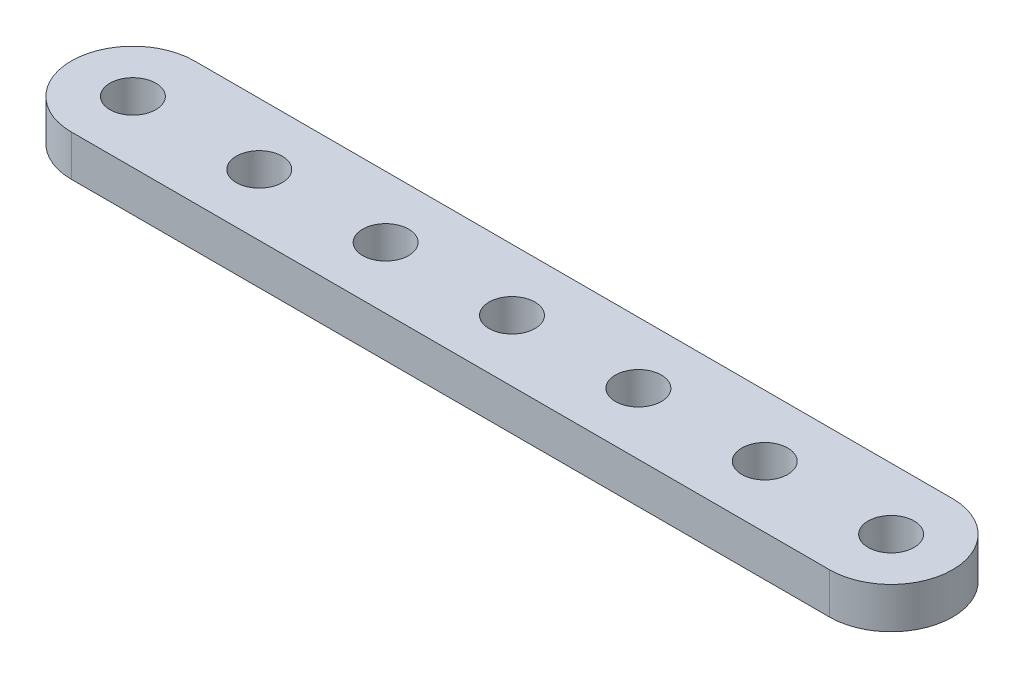
SolidWorks part; units mm, degrees
ref_plane "Front Plane" through (0, 0, 0) normal (0, 0, 1) x (1, 0, 0)
ref_plane "Top Plane" through (0, 0, 0) normal (0, 1, 0) x (1, 0, 0)
ref_plane "Right Plane" through (0, 0, 0) normal (1, 0, 0) x (0, 0, -1)
ref_plane "Plane1" through (0, 0, 0) normal (0, -1, 0) x (1, 0, 0)
sketch "Sketch1" plane through (0, 0, 0) normal (0, -1, 0) x (1, 0, 0)
  line L0 (-29.337, -4.7625) -> (29.337, -4.7625)
  line L1 (29.337, 4.7625) -> (-29.337, 4.7625)
  arc A0 (29.337, -4.7625) -> (29.337, 4.7625) centre (29.337, 0) ccw
  arc A1 (-29.337, 4.7625) -> (-29.337, -4.7625) centre (-29.337, 0) ccw
  circle A2 centre (29.337, 0) radius 1.778
  circle A3 centre (19.558, 0) radius 1.778
  circle A4 centre (9.779, 0) radius 1.778
  circle A5 centre (0, 0) radius 1.778
  circle A6 centre (-9.779, 0) radius 1.778
  circle A7 centre (-19.558, 0) radius 1.778
  circle A8 centre (-29.337, 0) radius 1.778
extrude "Boss-Extrude1" add sketch "Sketch1" against normal blind 6.35
sketch "Sketch2" plane through (0, 6.35, 0) normal (0, 1, 0) x (1, 0, 0)
  line L1 (-50.5984, -9.768) -> (41.2211, -9.768)
  line L2 (-50.5984, -9.768) -> (-50.5984, 10.9402)
  line L3 (-50.5984, 10.9402) -> (41.2211, 10.9402)
  line L4 (41.2211, -9.768) -> (41.2211, 10.9402)
extrude "Cut-Extrude1" cut sketch "Sketch2" against normal blind 3.175
